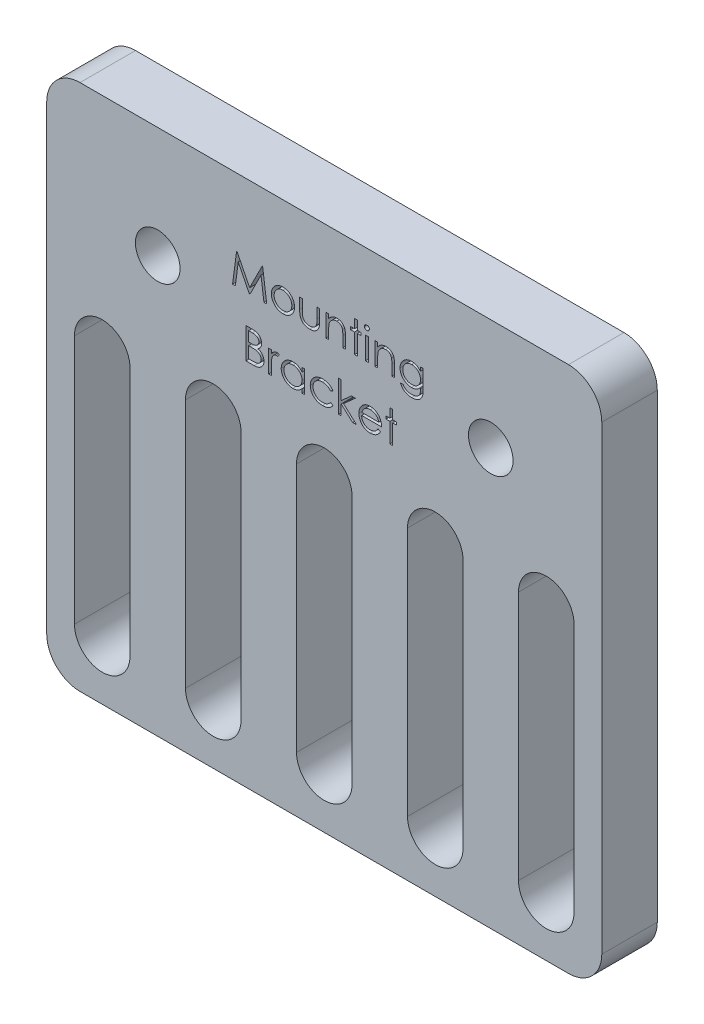
SolidWorks part; units mm, degrees
ref_plane "Front Plane" through (0, 0, 0) normal (0, 0, 1) x (1, 0, 0)
ref_plane "Top Plane" through (0, 0, 0) normal (0, 1, 0) x (1, 0, 0)
ref_plane "Right Plane" through (0, 0, 0) normal (1, 0, 0) x (0, 0, -1)
sketch "Sketch1" plane through (0, 0, 0) normal (0, 0, 1) x (1, 0, 0)
  line L1 (-99.721, 51.7634) -> (-36.221, 51.7634)
  line L2 (-99.721, 51.7634) -> (-99.721, -8.5616)
  line L3 (-99.721, -8.5616) -> (-36.221, -8.5616)
  line L4 (-36.221, 51.7634) -> (-36.221, -8.5616)
  dimension "D1" = 63.5
  dimension "D2" = 60.325
extrude "Boss-Extrude1" add sketch "Sketch1" along normal blind 6.35
sketch "Sketch2" plane through (0, 0, 6.35) normal (0, 0, 1) x (1, 0, 0)
  line L2 (-36.221, 51.7634) -> (-99.721, 51.7634) construction
  line L3 (-99.721, 51.7634) -> (-99.721, -8.5616) construction
  line L4 (-93.371, 26.3634) -> (-93.371, -2.2116) construction
  line L5 (-90.196, 26.3634) -> (-90.196, -2.2116)
  line L6 (-96.546, 26.3634) -> (-96.546, -2.2116)
  line L7 (-99.721, -8.5616) -> (-36.221, -8.5616) construction
  line L8 (-80.671, 26.3634) -> (-80.671, -2.2116) construction
  line L9 (-77.496, 26.3634) -> (-77.496, -2.2116)
  line L10 (-83.846, 26.3634) -> (-83.846, -2.2116)
  line L11 (-67.971, 26.3634) -> (-67.971, -2.2116) construction
  line L12 (-64.796, 26.3634) -> (-64.796, -2.2116)
  line L13 (-71.146, 26.3634) -> (-71.146, -2.2116)
  line L14 (-55.271, 26.3634) -> (-55.271, -2.2116) construction
  line L15 (-52.096, 26.3634) -> (-52.096, -2.2116)
  line L16 (-58.446, 26.3634) -> (-58.446, -2.2116)
  line L17 (-42.571, 26.3634) -> (-42.571, -2.2116) construction
  line L18 (-39.396, 26.3634) -> (-39.396, -2.2116)
  line L19 (-45.746, 26.3634) -> (-45.746, -2.2116)
  circle A0 centre (-87.021, 39.0634) radius 2.5527
  arc A1 (-90.196, 26.3634) -> (-96.546, 26.3634) centre (-93.371, 26.3634) ccw
  arc A2 (-96.546, -2.2116) -> (-90.196, -2.2116) centre (-93.371, -2.2116) ccw
  arc A3 (-77.496, 26.3634) -> (-83.846, 26.3634) centre (-80.671, 26.3634) ccw
  arc A4 (-83.846, -2.2116) -> (-77.496, -2.2116) centre (-80.671, -2.2116) ccw
  arc A5 (-64.796, 26.3634) -> (-71.146, 26.3634) centre (-67.971, 26.3634) ccw
  arc A6 (-71.146, -2.2116) -> (-64.796, -2.2116) centre (-67.971, -2.2116) ccw
  arc A7 (-52.096, 26.3634) -> (-58.446, 26.3634) centre (-55.271, 26.3634) ccw
  arc A8 (-58.446, -2.2116) -> (-52.096, -2.2116) centre (-55.271, -2.2116) ccw
  arc A9 (-39.396, 26.3634) -> (-45.746, 26.3634) centre (-42.571, 26.3634) ccw
  arc A10 (-45.746, -2.2116) -> (-39.396, -2.2116) centre (-42.571, -2.2116) ccw
  circle A11 centre (-48.921, 39.0634) radius 2.5527
  point P8 (-93.371, 12.0759)
  point P19 (-80.671, 12.0759)
  point P26 (-67.971, 12.0759)
  point P33 (-55.271, 12.0759)
  point P40 (-42.571, 12.0759)
  dimension "D1" = 5.1054
  dimension "D2" = 12.7
  dimension "D4" = 6.35
  dimension "D5" = 6.35
  dimension "D7" = 5
  dimension "D3" = 12.7
  dimension "D6" = 28.575
  dimension "D8" = 2
extrude "Cut-Extrude1" cut sketch "Sketch2" against normal through all
fillet "Fillet2" radius 3.81 1 edges at (-36.221, 51.7634, 3.175)
fillet "Fillet3" radius 3.81 3 edges at (-36.221, -8.5616, 3.175) (-99.721, -8.5616, 3.175) (-99.721, 51.7634, 3.175)
sketch "Sketch3" plane through (0, 0, 6.35) normal (0, 0, 1) x (1, 0, 0)
  text T0 " Mounting \r\n  Bracket"
extrude "Cut-Extrude5" cut sketch "Sketch3" against normal offset from surface (6.35 mm away) 6.35 up to face at (-46.3683, 39.0634, 6.35)
sketch "Sketch4" plane through (0, -8.5616, 0) normal (0, -1, 0) x (-1, 0, 0)
  line L0 (95.911, -3.175) -> (40.031, -3.175) construction
  line L1 (95.911, -6.35) -> (95.911, 0) construction
  line L2 (40.031, 0) -> (40.031, -6.35) construction
  line L3 (95.911, -6.35) -> (40.031, -6.35) construction
  line L4 (99.721, 0) -> (99.721, -6.35) construction
  circle A0 centre (87.021, -3.175) radius 1.7272
  circle A1 centre (74.321, -3.175) radius 1.7272
  circle A2 centre (61.621, -3.175) radius 1.7272
  circle A3 centre (48.921, -3.175) radius 1.7272
  dimension "D1" = 3.4544
  dimension "D2" = 3.175
  dimension "D3" = 12.7
  dimension "D4" = 4
extrude "Cut-Extrude6" cut sketch "Sketch4" against normal blind 6.35
